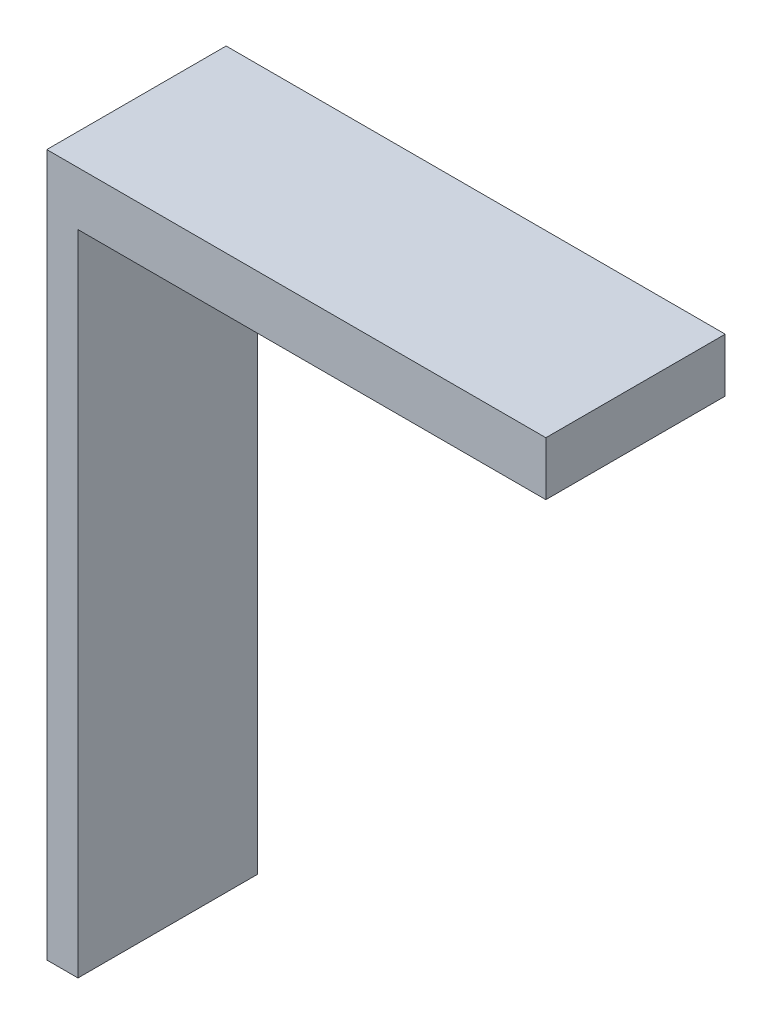
SolidWorks part; units mm, degrees
ref_plane "Front Plane" through (0, 0, 0) normal (0, 0, 1) x (1, 0, 0)
ref_plane "Top Plane" through (0, 0, 0) normal (0, 1, 0) x (1, 0, 0)
ref_plane "Right Plane" through (0, 0, 0) normal (1, 0, 0) x (0, 0, -1)
sketch "Sketch1" plane through (0, 0, 0) normal (0, 0, 1) x (1, 0, 0)
  line L1 (-2, -45) -> (2, -45)
  line L2 (-2, -45) -> (-2, 45)
  line L3 (-2, 45) -> (2, 45)
  line L4 (2, -45) -> (2, 45)
  line L5 (-2, -45) -> (2, 45) construction
  line L6 (-2, 45) -> (2, -45) construction
  point P0 (0, 0)
  dimension "D1" = 4
  dimension "D2" = 90
extrude "Boss-Extrude1" add sketch "Sketch1" along normal blind 23
sketch "Sketch2" plane through (2, 0, 0) normal (1, 0, 0) x (0, 0, -1)
  line L0 (0, -45) -> (0, 45) construction
  line L1 (-23, 45) -> (0, 45)
  line L2 (-23, 45) -> (-23, 38.1165)
  line L3 (-23, 38.1165) -> (0, 38.1165)
  line L4 (0, 45) -> (0, 38.1165)
extrude "Boss-Extrude2" add sketch "Sketch2" along normal blind 60
